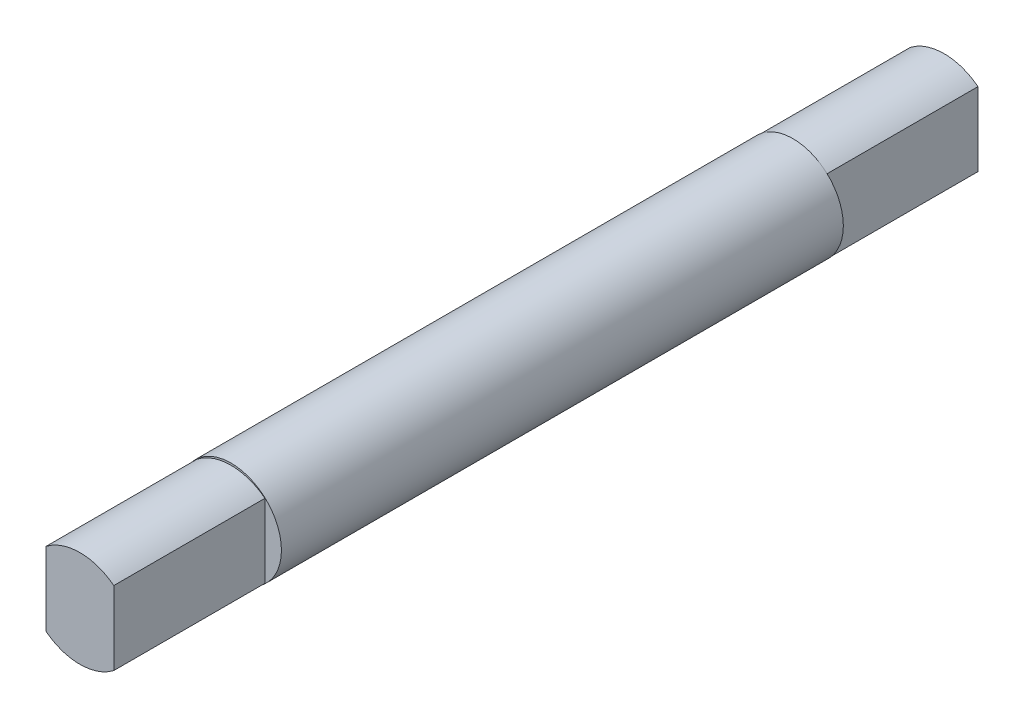
SolidWorks part; units mm, degrees
material "AISI 1020"
ref_plane "前视基准面" through (0, 0, 0) normal (0, 0, 1) x (1, 0, 0)
ref_plane "上视基准面" through (0, 0, 0) normal (0, 1, 0) x (1, 0, 0)
ref_plane "右视基准面" through (0, 0, 0) normal (1, 0, 0) x (0, 0, -1)
sketch "草图1" plane through (0, 0, 0) normal (0, 1, 0) x (1, 0, 0)
  line L1 (0, 0) -> (2.6, 0)
  line L2 (0, 0) -> (0, 14.5)
  line L3 (0, 14.5) -> (2.6, 14.5)
  line L4 (2.6, 0) -> (2.6, 14.5)
  dimension "D1" = 2.6
  dimension "D2" = 14.5
revolve "旋转1" add sketch "草图1" angle 360 about L2
sketch "草图2" plane through (0, 0, 0) normal (0, 0, 1) x (1, 0, 0)
  line L1 (-1.75, 1.9) -> (1.75, 1.9) construction
  line L2 (-1.75, 1.9) -> (-1.75, -1.9)
  line L3 (-1.75, -1.9) -> (1.75, -1.9) construction
  line L4 (1.75, 1.9) -> (1.75, -1.9)
  line L5 (-1.75, 1.9) -> (1.75, -1.9) construction
  line L6 (-1.75, -1.9) -> (1.75, 1.9) construction
  line L7 (-1.75, 2.5) -> (1.75, 2.5) construction
  line L8 (-1.75, 2.5) -> (-1.75, -2.5) construction
  line L9 (-1.75, -2.5) -> (1.75, -2.5) construction
  line L10 (1.75, 2.5) -> (1.75, -2.5) construction
  line L11 (-1.75, 2.5) -> (1.75, -2.5) construction
  line L12 (-1.75, -2.5) -> (1.75, 2.5) construction
  arc A0 (-1.75, 1.9) -> (1.75, 1.9) centre (0, -0.3521) cw
  arc A1 (-1.75, -1.9) -> (1.75, -1.9) centre (0, 0.3521) ccw
  point P0 (0, 0)
  point P6 (0, 0)
  dimension "D1" = 3.8
  dimension "D2" = 3.5
  dimension "D3" = 0.6
extrude "凸台-拉伸1" add sketch "草图2" along normal blind 7.8 contours L4 A1 L2 A0
mirror "镜向1" about plane through (0, 0, -14.5) normal (0, 0, -1) of bodies 107
